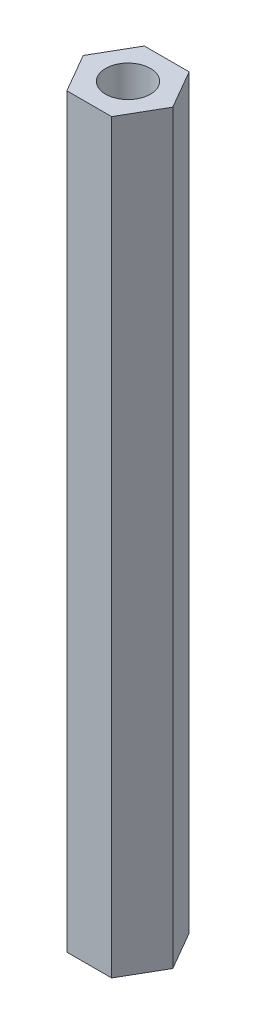
SolidWorks part; units mm, degrees
ref_plane "Front Plane" through (0, 0, 0) normal (0, 0, 1) x (1, 0, 0)
ref_plane "Top Plane" through (0, 0, 0) normal (0, 1, 0) x (1, 0, 0)
ref_plane "Right Plane" through (0, 0, 0) normal (1, 0, 0) x (0, 0, -1)
sketch "Sketch1" plane through (0, 0, 0) normal (0, 1, 0) x (1, 0, 0)
  line L1 (1.5, 2.5981) -> (-1.5, 2.5981)
  line L2 (-1.5, 2.5981) -> (-3, 0)
  line L3 (-3, 0) -> (-1.5, -2.5981)
  line L4 (-1.5, -2.5981) -> (1.5, -2.5981)
  line L5 (1.5, -2.5981) -> (3, 0)
  line L6 (3, 0) -> (1.5, 2.5981)
  circle A0 centre (0, 0) radius 2.5981 construction
  circle A1 centre (0, 0) radius 1.5
  circle A2 centre (0, 0) radius 3 construction
  dimension "D1" = 3
  dimension "D2" = 6
extrude "Boss-Extrude1" add sketch "Sketch1" along normal blind 50
